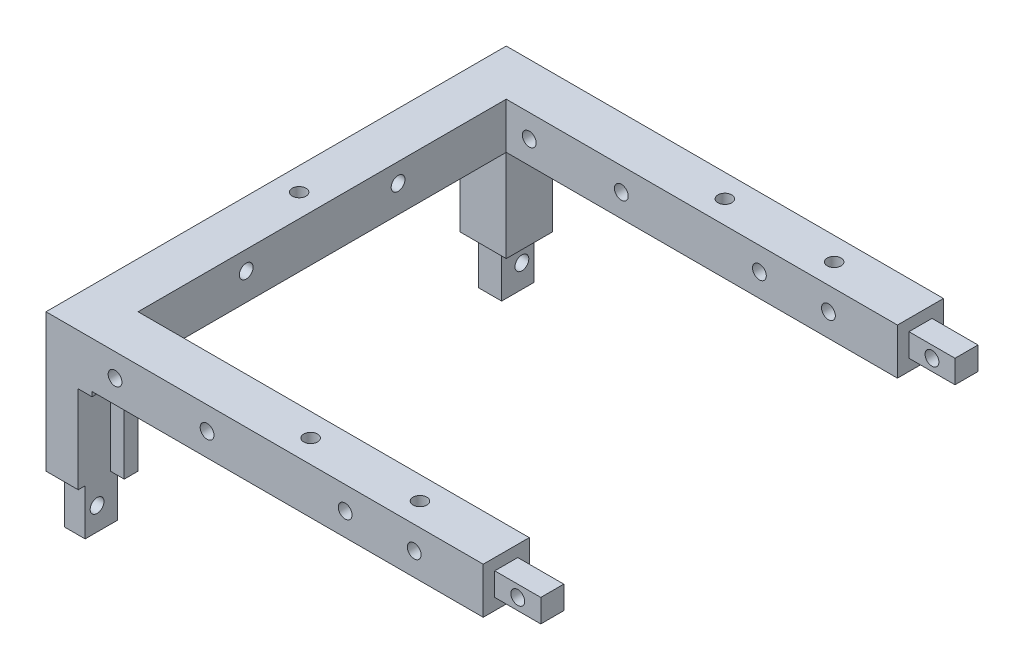
SolidWorks part; units mm, degrees
ref_plane "Front Plane" through (0, 0, 0) normal (0, 0, 1) x (1, 0, 0)
ref_plane "Top Plane" through (0, 0, 0) normal (0, 1, 0) x (1, 0, 0)
ref_plane "Right Plane" through (0, 0, 0) normal (1, 0, 0) x (0, 0, -1)
sketch "Sketch1" plane through (0, 0, 0) normal (0, 1, 0) x (1, 0, 0)
  line L0 (0, 0) -> (0, 200)
  line L1 (0, 200) -> (320, 200)
  line L2 (320, 200) -> (320, 0)
  line L3 (320, 0) -> (0, 0)
  line L4 (300, 20) -> (20, 20)
  line L5 (20, 20) -> (20, 180)
  line L6 (20, 180) -> (300, 180)
  line L7 (300, 180) -> (300, 20)
  dimension "D1" = 280
  dimension "D2" = 320
  dimension "D3" = 200
  dimension "D4" = 160
  dimension "D5" = 20
  dimension "D6" = 20
extrude "Boss-Extrude1" add sketch "Sketch1" along normal blind 20
sketch "Sketch2" plane through (0, 20, 0) normal (0, 1, 0) x (1, 0, 0)
  line L5 (0, 0) -> (320, 0) construction
  line L6 (320, 200) -> (190, 200)
  line L7 (320, 200) -> (320, 0)
  line L8 (320, 0) -> (190, 0)
  line L9 (190, 200) -> (190, 0)
  dimension "D1" = 130
extrude "Cut-Extrude1" cut sketch "Sketch2" against normal blind 20
sketch "Sketch5" plane through (0, 0, 0) normal (0, -1, 0) x (1, 0, 0)
  line L0 (0, -100) -> (110.8242, -100) construction
  line L1 (0, -200) -> (0, 0) construction
  line L3 (0, 0) -> (20, 0)
  line L4 (0, 0) -> (0, -20)
  line L5 (0, -20) -> (20, -20)
  line L6 (20, 0) -> (20, -20)
  line L14 (0, -180) -> (20, -180)
  line L15 (20, -200) -> (20, -180)
  line L16 (0, -200) -> (20, -200)
  line L17 (0, -200) -> (0, -180)
extrude "Boss-Extrude4" add sketch "Sketch5" along normal blind 40
sketch "Sketch8" plane through (0, -40, 0) normal (0, -1, 0) x (1, 0, 0)
  line L0 (0, -20) -> (20, -20) construction
  line L1 (15, -3) -> (5, -3)
  line L2 (15, -3) -> (15, -17)
  line L3 (15, -17) -> (5, -17)
  line L4 (5, -3) -> (5, -17)
  line L5 (20, -20) -> (20, 0) construction
  dimension "D1" = 14
  dimension "D2" = 10
  dimension "D3" = 3
  dimension "D4" = 5
extrude "Boss-Extrude5" add sketch "Sketch8" along normal blind 20
sketch "Sketch9" plane through (0, -40, 0) normal (0, -1, 0) x (1, 0, 0)
  line L0 (20, -200) -> (20, -180) construction
  line L1 (15, -183) -> (5, -183)
  line L2 (15, -183) -> (15, -197)
  line L3 (15, -197) -> (5, -197)
  line L4 (5, -183) -> (5, -197)
  line L5 (0, -200) -> (20, -200) construction
  dimension "D1" = 14
  dimension "D2" = 10
  dimension "D3" = 5
  dimension "D4" = 3
extrude "Boss-Extrude6" add sketch "Sketch9" along normal blind 20
sketch "Sketch10" plane through (190, 0, 0) normal (1, 0, 0) x (0, 0, -1)
  line L0 (180, 20) -> (180, 0) construction
  line L1 (195, 15) -> (185, 15)
  line L2 (195, 15) -> (195, 5)
  line L3 (195, 5) -> (185, 5)
  line L4 (185, 15) -> (185, 5)
  line L5 (200, 0) -> (180, 0) construction
  line L6 (180, 20) -> (20, 20) construction
  line L7 (20, 20) -> (100, 20) construction
  line L8 (100, 20) -> (100, -48.6073) construction
  line L9 (5, 5) -> (15, 5)
  line L10 (15, 15) -> (15, 5)
  line L11 (5, 15) -> (15, 15)
  line L12 (5, 15) -> (5, 5)
  dimension "D1" = 10
  dimension "D2" = 10
  dimension "D3" = 5
  dimension "D4" = 5
extrude "Boss-Extrude7" add sketch "Sketch10" along normal blind 20
sketch "Sketch11" plane through (0, 20, 0) normal (0, 1, 0) x (1, 0, 0)
  line L0 (0, 100) -> (227.0659, 100) construction
  line L1 (0, 200) -> (0, 0) construction
  line L2 (190, 200) -> (190, 180) construction
  line L3 (190, 200) -> (0, 200) construction
  circle A0 centre (152.5, 190) radius 3
  circle A1 centre (105, 190) radius 3
  circle A2 centre (10, 100) radius 3
  circle A3 centre (152.5, 10) radius 3
  circle A4 centre (105, 10) radius 3
  dimension "D1" = 6
  dimension "D2" = 6
  dimension "D3" = 6
  dimension "D7" = 10
  dimension "D8" = 10
  dimension "D4" = 37.5
  dimension "D5" = 85
  dimension "D6" = 10
extrude "Cut-Extrude2" cut sketch "Sketch11" against normal blind 30
sketch "Sketch13" plane through (0, 0, 0) normal (-1, 0, 0) x (0, 0, 1)
  line L0 (-100, 20) -> (-100, -73.9116) construction
  line L1 (-200, 20) -> (0, 20) construction
  line L2 (-180, 20) -> (-20, 20) construction
  line L3 (-3, -60) -> (-17, -60) construction
  line L4 (-3, -60) -> (-3, -40) construction
  circle A1 centre (-8.2, -50) radius 3
  circle A2 centre (-67, 11.8) radius 3
  circle A3 centre (-133, 11.8) radius 3
  circle A4 centre (-191.8, -50) radius 3
  dimension "D1" = 6
  dimension "D2" = 6
  dimension "D5" = 8.2
  dimension "D6" = 8.2
  dimension "D7" = 6
  dimension "D9" = 5.2
  dimension "D3" = 33
  dimension "D4" = 33
  dimension "D8" = 10
extrude "Cut-Extrude3" cut sketch "Sketch13" against normal blind 30
sketch "Sketch14" plane through (0, 0, -200) normal (0, 0, -1) x (-1, 0, 0)
  line L0 (0, 20) -> (0, -40) construction
  line L1 (-190, 0) -> (-20, 0) construction
  line L2 (-190, 20) -> (0, 20) construction
  circle A0 centre (-160, 10) radius 3
  circle A1 centre (-30, 10) radius 3
  circle A2 centre (-70, 10) radius 3
  circle A3 centre (-130, 10) radius 3
  dimension "D1" = 160
  dimension "D2" = 6
  dimension "D3" = 10
  dimension "D4" = 10
  dimension "D5" = 6
  dimension "D6" = 30
  dimension "D7" = 6
  dimension "D8" = 6
  dimension "D9" = 10
  dimension "D10" = 10
  dimension "D11" = 70
  dimension "D12" = 130
extrude "Cut-Extrude4" cut sketch "Sketch14" against normal through all both and the other way through all
sketch "Sketch16" plane through (0, 0, -5) normal (0, 0, 1) x (1, 0, 0)
  line L1 (210, 5) -> (190, 5) construction
  line L2 (190, 15) -> (190, 5) construction
  circle A0 centre (200, 10) radius 3
  dimension "D1" = 10
  dimension "D2" = 5
  dimension "D3" = 6
extrude "Cut-Extrude5" cut sketch "Sketch16" against normal through all both and the other way through all
sketch "Sketch19" plane through (20, 0, 0) normal (1, 0, 0) x (0, 0, -1)
  line L1 (0, -40) -> (14, -40)
  line L2 (0, -40) -> (0, -2)
  line L3 (0, -2) -> (14, -2)
  line L4 (14, -40) -> (14, -2)
  dimension "D1" = 38
  dimension "D2" = 14
extrude "Cut-Extrude8" cut sketch "Sketch19" against normal blind 5
sketch "Sketch20" plane through (15, 0, 0) normal (1, 0, 0) x (0, 0, -1)
  line L0 (0, -2) -> (0, -40)
  line L1 (0, -40) -> (3, -40)
  line L2 (3, -40) -> (3, -60)
  line L3 (3, -60) -> (17, -60)
  line L4 (17, -60) -> (17, -40)
  line L5 (17, -40) -> (14, -40)
  line L6 (14, -40) -> (14, -2)
  line L7 (14, -2) -> (0, -2)
extrude "Cut-Extrude9" cut sketch "Sketch20" against normal blind 1
